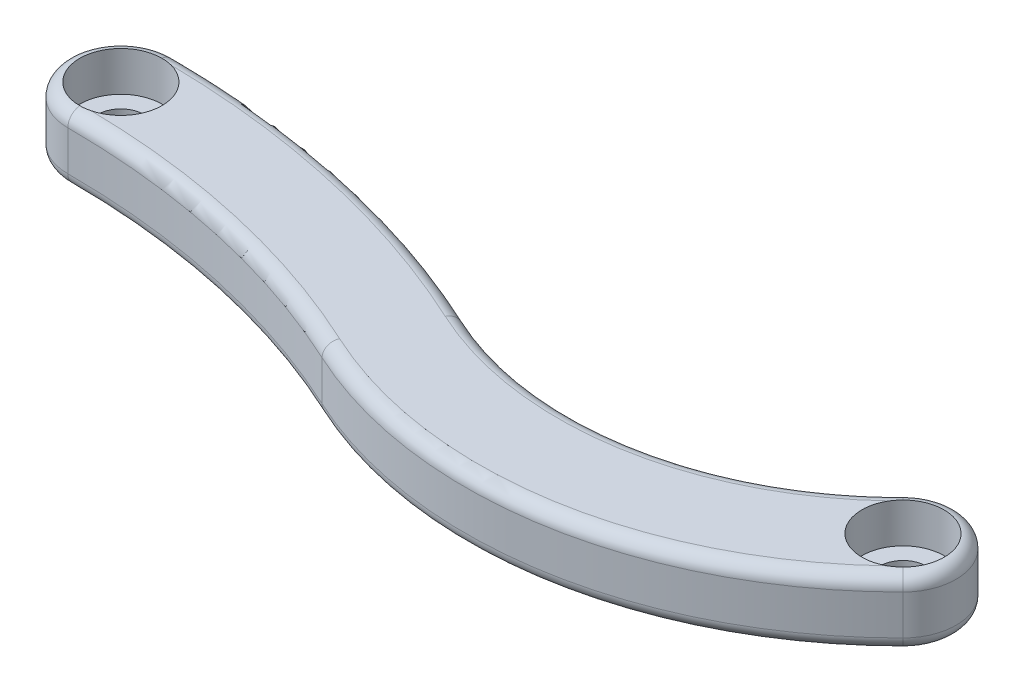
SolidWorks part; units mm, degrees
material "Rubber"
ref_plane "Front Plane" through (0, 0, 0) normal (0, 0, 1) x (1, 0, 0)
ref_plane "Top Plane" through (0, 0, 0) normal (0, 1, 0) x (1, 0, 0)
ref_plane "Right Plane" through (0, 0, 0) normal (1, 0, 0) x (0, 0, -1)
sketch "Sketch1" plane through (0, 0, 0) normal (0, 1, 0) x (1, 0, 0)
  line L0 (-29.5, 0) -> (29.5, 0) construction
  line L3 (26.029, 3.471) -> (-3.1174, 32.6174) construction
  circle A2 centre (-29.5, 0) radius 1.75
  circle A3 centre (29.5, 0) radius 1.75
  arc A4 (-29.5, 4) -> (-29.5, -4) centre (-29.5, 0) ccw
  arc A5 (32.3284, -2.8284) -> (26.6716, 2.8284) centre (29.5, 0) ccw
  arc A7 (-1.5267, -2.1725) -> (26.6716, 2.8284) centre (8.9939, 20.5061) ccw
  arc A9 (-4.8932, -9.4296) -> (32.3284, -2.8284) centre (8.9939, 20.5061) ccw
  arc A10 (-29.5, 4) -> (-1.5267, -2.1725) centre (-29.5, -62.4731) cw
  arc A11 (-29.5, -4) -> (-4.8932, -9.4296) centre (-29.5, -62.4731) cw
  dimension "D1" = 3.5
  dimension "D8" = 33
  dimension "D2" = 59
  dimension "D3" = 29.5
  dimension "D4" = 8
  dimension "D6" = 8
  dimension "D5" = 45
  dimension "D7" = 8
extrude "Boss-Extrude1" add sketch "Sketch1" along normal blind 5
fillet "Fillet1" radius 1 12 edges at (32.3284, 5, -2.8284) (14.7565, 5, 11.9869) (-16.9007, 5, 5.3735) (-33.5, 5, 0) (-15.1769, 5, -2.4385) (32.3284, 0, -2.8284) (14.7565, 0, 11.9869) (-16.9007, 0, 5.3735) (-33.5, 0, 0) (-15.1769, 0, -2.4385) (13.3595, 5, 4.1098) (13.3595, 0, 4.1098)
sketch "Sketch2" plane through (0, 0, 0) normal (0, -1, 0) x (1, 0, 0)
  circle A0 centre (29.5, 0) radius 3.1
  circle A1 centre (-29.5, 0) radius 3.1
  dimension "D2" = 6.2
extrude "Cut-Extrude1" cut sketch "Sketch2" against normal blind 3
ref_plane "Plane1" through (0, -10, 0) normal (0, -1, 0) x (-1, 0, 0)
mirror "Mirror1" about plane through (0, -10, 0) normal (0, -1, 0) of bodies 103
sketch "Sketch3" plane through (0, 0, 0) normal (0, -1, 0) x (1, 0, 0)
  line L1 (-37.4742, -12.0484) -> (46.2014, -12.0484)
  line L2 (-37.4742, -12.0484) -> (-37.4742, 15.7603)
  line L3 (-37.4742, 15.7603) -> (46.2014, 15.7603)
  line L4 (46.2014, -12.0484) -> (46.2014, 15.7603)
extrude "Cut-Extrude2" cut sketch "Sketch3" against normal up to surface (5 mm away) up to face at (-0.8067, 5, 2.8184)
equation "\"D3@Sketch1\"=\"D2@Sketch1\"/2"
